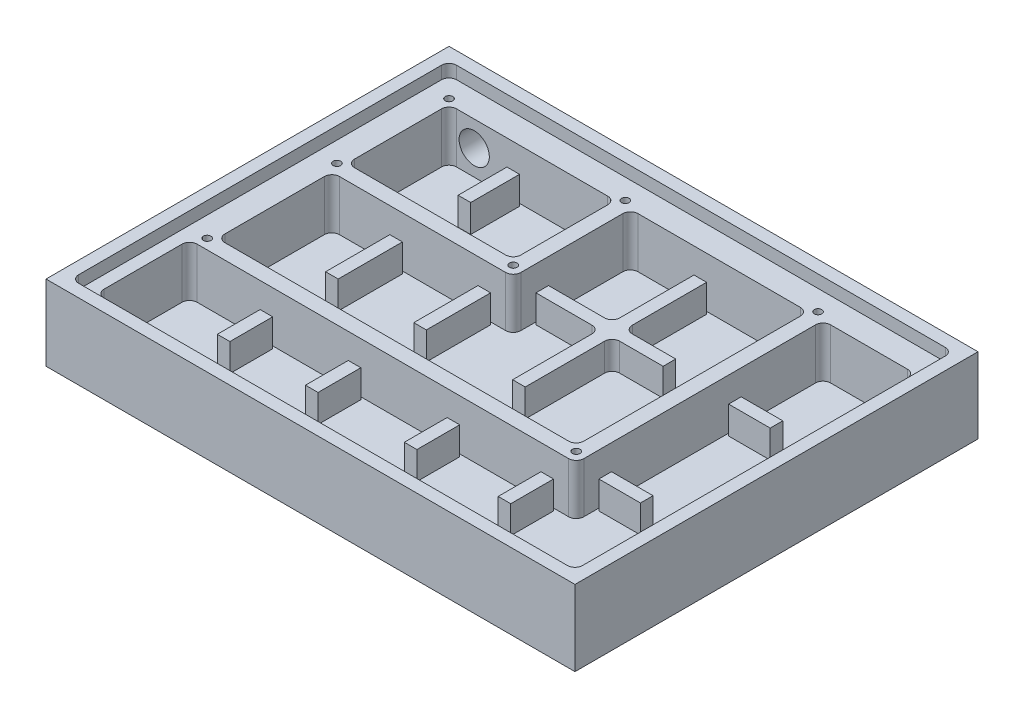
SolidWorks part; units mm, degrees
ref_plane "Front Plane" through (0, 0, 0) normal (0, 0, 1) x (1, 0, 0)
ref_plane "Top Plane" through (0, 0, 0) normal (0, 1, 0) x (1, 0, 0)
ref_plane "Right Plane" through (0, 0, 0) normal (1, 0, 0) x (0, 0, -1)
sketch "Sketch2" plane through (0, 0, 0) normal (0, 1, 0) x (1, 0, 0)
  line L1 (-100, 75) -> (100, 75)
  line L2 (-100, 75) -> (-100, -75)
  line L3 (-100, -75) -> (100, -75)
  line L4 (100, 75) -> (100, -75)
  line L5 (-100, 75) -> (100, -75) construction
  line L6 (-100, -75) -> (100, 75) construction
  point P0 (0, 0)
  dimension "D1" = 200
  dimension "D2" = 150
sketch "Sketch1" plane through (0, 0, 0) normal (0, 1, 0) x (1, 0, 0)
  line L1 (-105, -80) -> (105, -80)
  line L2 (-105, -80) -> (-105, 80)
  line L3 (-105, 80) -> (105, 80)
  line L4 (105, -80) -> (105, 80)
  line L5 (-105, -80) -> (105, 80) construction
  line L6 (-105, 80) -> (105, -80) construction
  point P0 (0, 0)
  dimension "D1" = 210
  dimension "D2" = 160
extrude "Boss-Extrude1" add sketch "Sketch1" along normal blind 30
sketch "Sketch9" plane through (0, 30, 0) normal (0, 1, 0) x (1, 0, 0)
  line L4 (100, 75) -> (-100, 75)
  line L5 (100, -75) -> (100, 75)
  line L6 (-100, -75) -> (100, -75)
  line L7 (-100, 75) -> (-100, -75)
  line L8 (100, 75) -> (-100, 75)
  line L9 (100, -75) -> (100, 75)
  line L10 (-100, -75) -> (100, -75)
  line L11 (-100, 75) -> (-100, -75)
  dimension "D1" = 0
extrude "Cut-Extrude3" cut sketch "Sketch9" against normal blind 5
sketch "Sketch3" plane through (0, 30, 0) normal (0, 1, 0) x (1, 0, 0)
  line L1 (-100, 75) -> (-100, -75) construction
  line L2 (-95, 70) -> (-19, 70) construction
  line L3 (-95, 70) -> (-95, 19.5) construction
  line L4 (-95, 19.5) -> (-19, 19.5) construction
  line L5 (-19, 70) -> (-19, 19.5) construction
  line L6 (-100, 75) -> (100, 75) construction
  circle A0 centre (-92, 67) radius 1.5
  circle A1 centre (-22, 67) radius 1.5
  circle A2 centre (-92, 22.5) radius 1.5
  circle A3 centre (-22, 22.5) radius 1.5
  dimension "D5" = 3
  dimension "D1" = 50.5
  dimension "D2" = 76
  dimension "D3" = 5
  dimension "D4" = 5
  dimension "D6" = 3
  dimension "D7" = 3
  dimension "D8" = 3
  dimension "D9" = 3
extrude "Cut-Extrude1" cut sketch "Sketch3" against normal blind 10
sketch "Sketch11" plane through (0, 30, 0) normal (0, 1, 0) x (1, 0, 0)
  line L1 (-95, 70) -> (57.5, 70)
  line L2 (-95, 70) -> (-95, -32)
  line L3 (-95, -32) -> (57.5, -32)
  line L4 (57.5, 70) -> (57.5, -32)
  dimension "D1" = 152.5
  dimension "D2" = 102
sketch "Sketch12" plane through (0, 30, 0) normal (0, 1, 0) x (1, 0, 0)
  line L0 (100, -75) -> (100, 75) construction
  line L1 (-95, 70) -> (95, 70)
  line L2 (-95, 70) -> (-95, -70)
  line L3 (-95, -70) -> (95, -70)
  line L4 (95, 70) -> (95, -70)
  line L5 (-100, -75) -> (100, -75) construction
  dimension "D1" = 5
  dimension "D2" = 5
extrude "Cut-Extrude4" cut sketch "Sketch12" against normal blind 25
sketch "Sketch13" plane through (0, 25, 0) normal (0, 1, 0) x (1, 0, 0)
  line L0 (-95, 19.5) -> (-19, 19.5)
  line L1 (-19, 19.5) -> (-19, 70)
  line L2 (-19, 70) -> (-95, 70)
  line L3 (-95, 70) -> (-95, 19.5)
extrude "Extrude-Thin1" add sketch "Sketch13" against normal blind 25 thin
sketch "Sketch14" plane through (0, 25, 0) normal (0, 1, 0) x (1, 0, 0)
  line L0 (-95, 19.5) -> (-95, -32)
  line L1 (-95, -32) -> (57.5, -32)
  line L2 (57.5, -32) -> (57.5, 70)
  line L3 (57.5, 70) -> (-19, 70)
extrude "Extrude-Thin2" add sketch "Sketch14" against normal blind 25 thin contours L3 | L0 L1 L2
sketch "Sketch15" plane through (0, 25, 0) normal (0, 1, 0) x (1, 0, 0)
  line L0 (-95, -32) -> (57.5, -32) construction
  line L2 (57.5, 70) -> (57.5, -32) construction
  circle A0 centre (54.5, 67) radius 1.5
  circle A1 centre (-92, -29) radius 1.5
  circle A2 centre (54.5, -29) radius 1.5
  circle A3 centre (-92, 67) radius 1.5
  circle A4 centre (-92, 22.5) radius 1.5
  circle A5 centre (-22, 22.5) radius 1.5
  circle A6 centre (-22, 67) radius 1.5
  dimension "D1" = 3
  dimension "D2" = 3
  dimension "D3" = 3
  dimension "D4" = 3
extrude "Cut-Extrude5" cut sketch "Sketch15" against normal blind 10
sketch "Sketch16" plane through (0, 25, 0) normal (0, 1, 0) x (1, 0, 0)
  line L0 (58.5, -33) -> (58.5, 70) construction
  line L1 (95, 70) -> (58.5, 70)
  line L2 (95, 70) -> (95, 65)
  line L3 (95, 65) -> (58.5, 65)
  line L4 (58.5, 70) -> (58.5, 65)
extrude "Boss-Extrude2" add sketch "Sketch16" against normal up to next
fillet "Fillet1" radius 3 14 edges at (95, 15, 70) (52.5, 15, -65) (-18, 15, -65) (52.5, 15, 27) (-95, 15, 70) (-90, 15, 27) (-90, 15, -24.5) (-24, 15, -24.5) (-24, 15, -65) (-95, 15, 33) (-90, 15, -18.5) (-90, 15, -65) (95, 15, -65) (58.5, 15, -65)
fillet "Fillet2" radius 3 2 edges at (58.5, 15, 33) (-18, 15, -18.5)
fillet "Fillet3" radius 3 4 edges at (100, 27.5, 75) (-100, 27.5, 75) (100, 27.5, -75) (-100, 27.5, -75)
sketch "Sketch17" plane through (0, 0, -80) normal (0, 0, -1) x (-1, 0, 0)
  line L0 (105, 30) -> (105, 0) construction
  circle A0 centre (80, 15) radius 6
  dimension "D1" = 12
  dimension "D2" = 25
extrude "Cut-Extrude6" cut sketch "Sketch17" against normal up to next
sketch "Sketch18" plane through (0, 25, 0) normal (0, 1, 0) x (1, 0, 0)
  line L0 (17.25, 55) -> (17.25, -17)
  line L1 (-22, 8.5) -> (-22, -17)
  line L2 (-87, -27) -> (49.5, -27) construction
  line L3 (-87, 18.5) -> (-21, 18.5) construction
  line L4 (49.5, 65) -> (-15, 65) construction
  line L5 (54.5, -43) -> (54.5, -60)
  line L6 (-57, 55) -> (-57, 35.6068)
  line L8 (-27, 65) -> (-87, 65) construction
  line L10 (-22, -43) -> (-22, -60)
  line L11 (17.25, -43) -> (17.25, -60)
  line L18 (-57, 8.5) -> (-57, -17)
  line L19 (-57, -43) -> (-57, -60)
  dimension "D1" = 10
  dimension "D2" = 10
  dimension "D3" = 10
  dimension "D4" = 10
extrude "Extrude-Thin3" add sketch "Sketch18" against normal blind 11 separate body thin thin type one direction reverse wall 5
sketch "Sketch19" plane through (0, 25, 0) normal (0, 1, 0) x (1, 0, 0)
  line L0 (-8, 22.5) -> (42.5, 22.5)
  line L1 (68.5, 22.5) -> (85, 22.5)
  line L2 (68.5, -29) -> (85, -29)
  line L3 (58.5, -30) -> (58.5, 62) construction
  line L4 (95, -67) -> (95, 62) construction
  line L5 (58.5, -30) -> (58.5, 62) construction
  line L6 (52.5, -24) -> (52.5, 62) construction
  line L7 (-18, 21.5) -> (-18, 62) construction
  dimension "D1" = 10
  dimension "D2" = 10
  dimension "D3" = 10
  dimension "D4" = 10
  dimension "D5" = 10
  dimension "D6" = 10
extrude "Extrude-Thin4" add sketch "Sketch19" against normal blind 11 thin
fillet "Fillet4" radius 3 4 edges at (17.25, 19.5, -22.5) (17.25, 19.5, -17.5) (22.25, 19.5, -17.5) (22.25, 19.5, -22.5)
